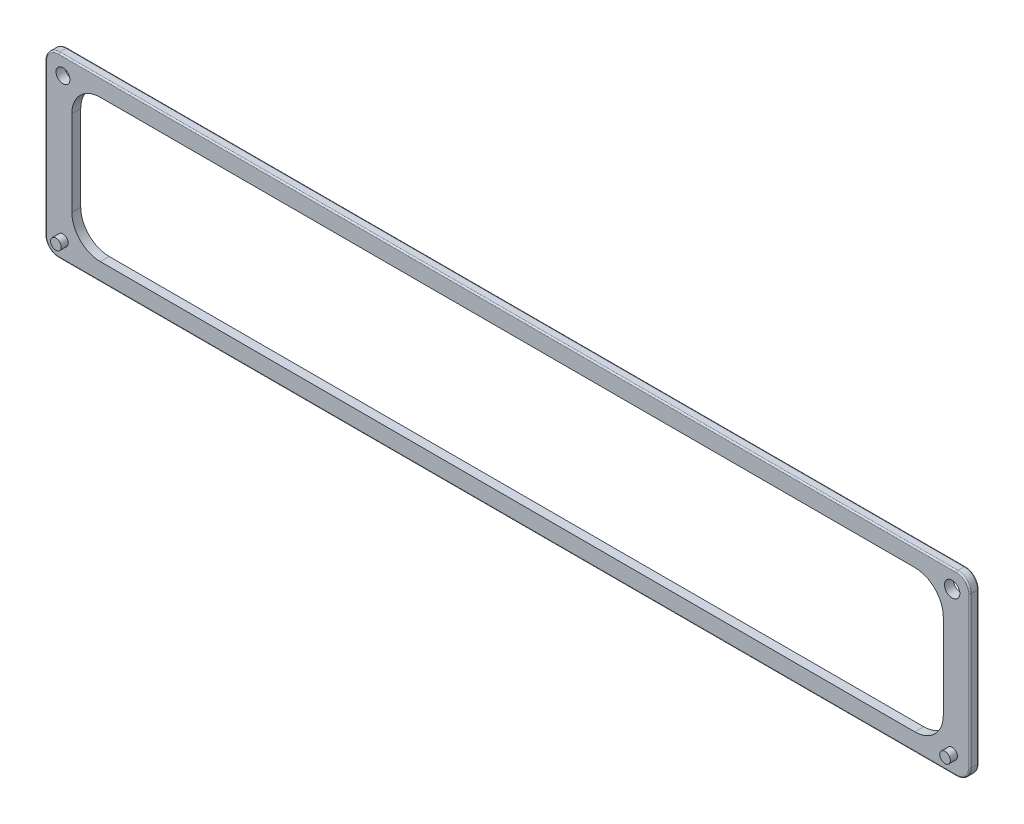
SolidWorks part; units mm, degrees
ref_plane "Front Plane" through (0, 0, 0) normal (0, 0, 1) x (1, 0, 0)
ref_plane "Top Plane" through (0, 0, 0) normal (0, 1, 0) x (1, 0, 0)
ref_plane "Right Plane" through (0, 0, 0) normal (1, 0, 0) x (0, 0, -1)
sketch "Sketch1" plane through (0, 0, 0) normal (0, 0, 1) x (1, 0, 0)
  line L1 (-41.275, 7.9375) -> (41.275, 7.9375)
  line L2 (-41.275, 7.9375) -> (-41.275, -7.9375)
  line L3 (-41.275, -7.9375) -> (41.275, -7.9375)
  line L4 (41.275, 7.9375) -> (41.275, -7.9375)
  line L5 (-41.275, 7.9375) -> (41.275, -7.9375) construction
  line L6 (-41.275, -7.9375) -> (41.275, 7.9375) construction
  point P0 (0, 0)
  dimension "D1" = 82.55
  dimension "D2" = 15.875
extrude "Boss-Extrude1" add sketch "Sketch1" along normal blind 0.7937
ref_plane "Plane1" through (0, 0, 0) normal (0, 1, 0) x (1, 0, 0)
ref_plane "Plane2" through (0, 0, 0) normal (1, 0, 0) x (0, 0, -1)
sketch "Sketch4" plane through (0, 0, 0.7937) normal (0, 0, 1) x (1, 0, 0)
  line L0 (41.275, -7.9375) -> (41.275, 7.9375) construction
  line L1 (41.275, 7.9375) -> (-41.275, 7.9375) construction
  circle A0 centre (39.6875, 6.35) radius 0.4746
  dimension "D3" = 0.9492
  dimension "D1" = 1.5875
  dimension "D2" = 1.5875
extrude "Boss-Extrude2" add sketch "Sketch4" along normal blind 0.635
mirror "Mirror1" about plane through (0, 0, 0) normal (0, 1, 0) of "Boss-Extrude2"
mirror "Mirror2" about plane through (0, 0, 0) normal (1, 0, 0) of "Boss-Extrude2", "Mirror1"
sketch "Sketch6" plane through (0, 0, 0.7937) normal (0, 0, 1) x (1, 0, 0)
  line L0 (41.275, 7.9375) -> (-41.275, 7.9375) construction
  line L1 (-36.3538, 6.35) -> (36.3538, 6.35)
  line L2 (-38.8938, 3.81) -> (-38.8938, -3.81)
  line L3 (-36.3538, -6.35) -> (36.3538, -6.35)
  line L4 (38.8938, 3.81) -> (38.8938, -3.81)
  line L5 (-38.8938, 6.35) -> (38.8938, -6.35) construction
  line L6 (-38.8938, -6.35) -> (38.8938, 6.35) construction
  line L7 (-41.275, 7.9375) -> (-41.275, -7.9375) construction
  arc A0 (36.3538, -6.35) -> (38.8938, -3.81) centre (36.3538, -3.81) ccw
  arc A1 (36.3538, 6.35) -> (38.8938, 3.81) centre (36.3538, 3.81) cw
  arc A2 (-38.8938, -3.81) -> (-36.3538, -6.35) centre (-36.3538, -3.81) ccw
  arc A3 (-38.8938, 3.81) -> (-36.3538, 6.35) centre (-36.3538, 3.81) cw
  point P0 (0, 0)
  dimension "D3" = 2.54
  dimension "D6" = 2.54
  dimension "D4" = 2.54
  dimension "D5" = 2.54
  dimension "D1" = 1.5875
  dimension "D2" = 2.3813
extrude "Cut-Extrude3" cut sketch "Sketch6" against normal through all
sketch "Sketch7" plane through (0, 0, 1.4287) normal (0, 0, 1) x (1, 0, 0)
  circle A0 centre (-39.6875, 6.35) radius 0.6223
  circle A1 centre (39.6875, 6.35) radius 0.6858
  dimension "D1" = 1.2446
  dimension "D2" = 1.3716
extrude "Cut-Extrude4" cut sketch "Sketch7" against normal through all
fillet "Fillet1" radius 1.1938 4 edges at (41.275, 7.9375, 0.3969) (41.275, -7.9375, 0.3969) (-41.275, -7.9375, 0.3969) (-41.275, 7.9375, 0.3969)
fillet "Fillet2" radius 0.127 16 edges at (-40.9253, 7.5878, 0.7937) (0, 7.9375, 0.7937) (40.9253, 7.5878, 0.7937) (41.275, 0, 0.7937) (40.9253, -7.5878, 0.7937) (0, -7.9375, 0.7937) (-40.9253, -7.5878, 0.7937) (-40.9253, 7.5878, 0) (0, 7.9375, 0) (40.9253, 7.5878, 0) (41.275, 0, 0) (40.9253, -7.5878, 0) (0, -7.9375, 0) (-40.9253, -7.5878, 0) (-41.275, 0, 0.7937) (-41.275, 0, 0)
